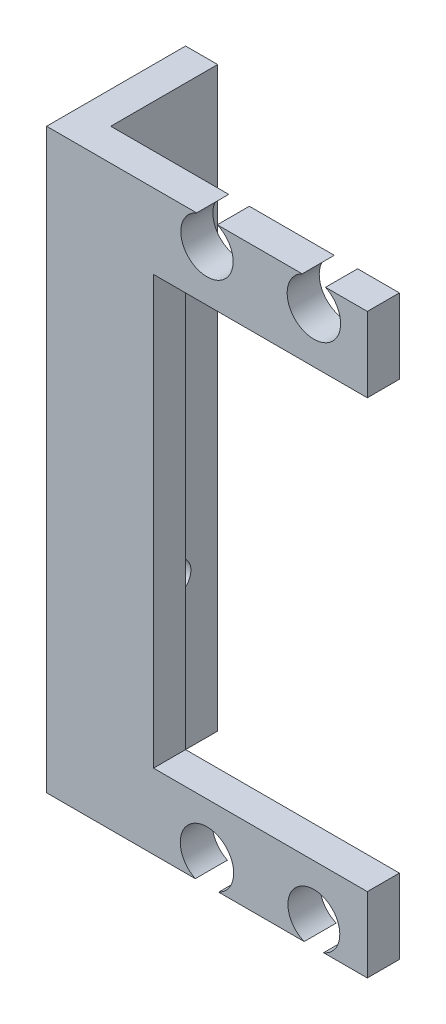
SolidWorks part; units mm, degrees
ref_plane "前视基准面" through (0, 0, 0) normal (0, 0, 1) x (1, 0, 0)
ref_plane "上视基准面" through (0, 0, 0) normal (0, 1, 0) x (1, 0, 0)
ref_plane "右视基准面" through (0, 0, 0) normal (1, 0, 0) x (0, 0, -1)
other "Configuration Table"
sketch "草图1" plane through (0, 0, 0) normal (0, 0, 1) x (1, 0, 0)
  line L0 (0, 0) -> (0, 54)
  line L1 (0, 54) -> (3, 54)
  line L2 (3, 54) -> (3, 0)
  line L3 (3, 0) -> (0, 0)
  dimension "D1" = 3
  dimension "D2" = 54
extrude "凸台-拉伸1" add sketch "草图1" along normal blind 13
sketch "草图3" plane through (3, 0, 0) normal (1, 0, 0) x (0, 0, -1)
  line L0 (-13, 27) -> (0, 27) construction
  line L1 (-13, 0) -> (-13, 54) construction
  line L2 (0, 0) -> (0, 54) construction
  line L6 (-16, -10.1) -> (139, -10.1) construction
  circle A0 centre (-4, 40.5) radius 1.5
  circle A3 centre (-4, 14.3) radius 1.5
  dimension "D2" = 3
  dimension "D4" = 3
  dimension "D5" = 9
  dimension "D6" = 24.4
  dimension "D1" = 13.5
  dimension "D3" = 4
extrude "切除-拉伸1" cut sketch "草图3" against normal through all
sketch "草图4" plane through (3, 0, 0) normal (1, 0, 0) x (0, 0, -1)
  line L0 (-13, 54) -> (-10, 54)
  line L1 (-13, 54) -> (0, 54) construction
  line L2 (-10, 54) -> (-10, 0)
  line L3 (-13, 0) -> (0, 0) construction
  line L4 (-10, 0) -> (-13, 0)
  line L5 (-13, 0) -> (-13, 54)
  dimension "D1" = 3
extrude "凸台-拉伸2" add sketch "草图4" along normal blind 27
sketch "草图5" plane through (0, 0, 13) normal (0, 0, 1) x (1, 0, 0)
  line L0 (30, 47) -> (10, 47)
  line L1 (30, 54) -> (30, 0) construction
  line L2 (10, 47) -> (10, 7)
  line L3 (10, 7) -> (30, 7)
  line L4 (30, 7) -> (30, 47)
  line L8 (10, 47) -> (30, 47) construction
  dimension "D1" = 20
  dimension "D2" = 40
extrude "切除-拉伸2" cut sketch "草图5" against normal through all
sketch "草图6" plane through (0, 0, 10) normal (0, 0, -1) x (-1, 0, 0)
  circle A0 centre (-25, 51.75) radius 2.5
  circle A1 centre (-25, 2.25) radius 2.4249
  circle A2 centre (-15, 51.75) radius 2.4476
  arc A3 (-16.0897, 54) -> (-13.9103, 54) centre (-15, 51.75) ccw construction
  arc A4 (-26.0897, 54) -> (-23.9103, 54) centre (-25, 51.75) ccw construction
  arc A5 (-23.9103, 0) -> (-26.0897, 0) centre (-25, 2.25) ccw construction
  circle A6 centre (-15, 2.25) radius 2.5
  arc A7 (-13.9103, 0) -> (-16.0897, 0) centre (-15, 2.25) ccw construction
extrude "切除-拉伸3" cut sketch "草图6" against normal through all
